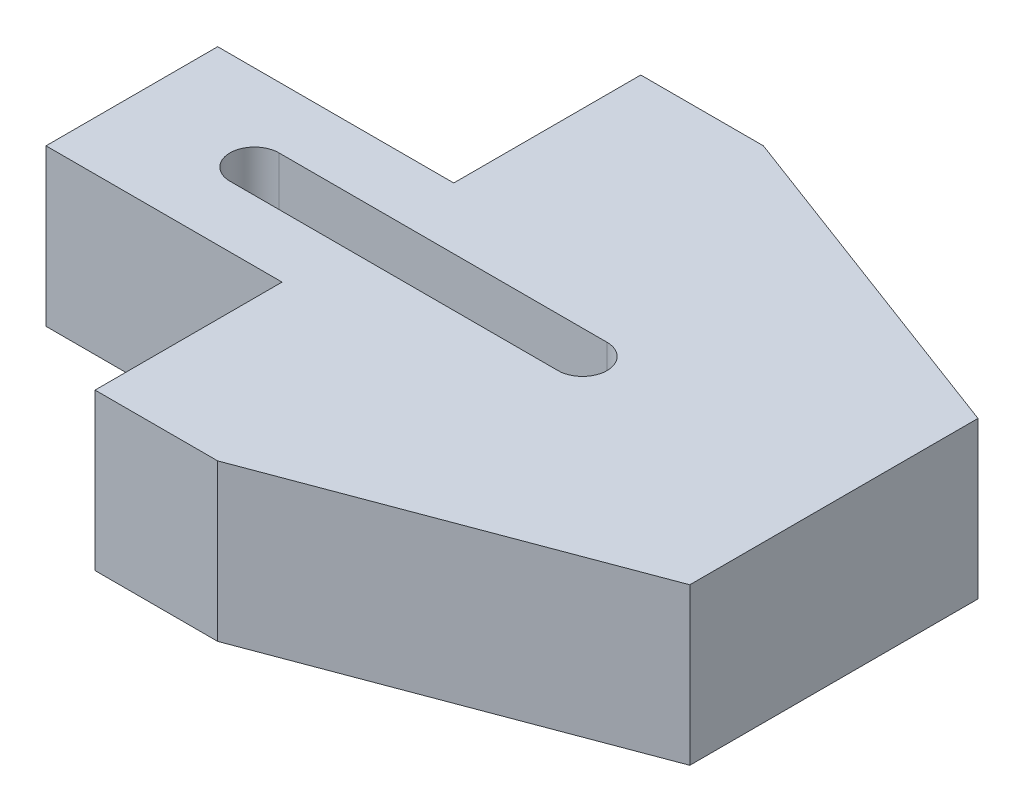
SolidWorks part; units mm, degrees
ref_plane "Front Plane" through (0, 0, 0) normal (0, 0, 1) x (1, 0, 0)
ref_plane "Top Plane" through (0, 0, 0) normal (0, 1, 0) x (1, 0, 0)
ref_plane "Right Plane" through (0, 0, 0) normal (1, 0, 0) x (0, 0, -1)
sketch "Sketch1" plane through (0, 0, 0) normal (0, 1, 0) x (1, 0, 0)
  line L0 (-22.9, 0) -> (-22.9, 2.8)
  line L1 (-22.9, 2.8) -> (-15.2, 2.8)
  line L2 (-15.2, 2.8) -> (-15.2, 8.9)
  line L3 (-15.2, 8.9) -> (-11.2, 8.9)
  line L4 (-11.2, 8.9) -> (0, 4.7)
  line L5 (0, 4.7) -> (0, 0)
  line L6 (0, 0) -> (-22.9, 0)
  point P11 (-22.9, 1.4)
  dimension "D1" = 22.9
  dimension "D2" = 15.2
  dimension "D3" = 2.8
  dimension "D4" = 8.9
  dimension "D5" = 4.7
  dimension "D6" = 4
extrude "Boss-Extrude1" add sketch "Sketch1" along normal mid plane 5.1
mirror "Mirror1" about plane through (0, 0, 0) normal (0, 0, 1) of "Boss-Extrude1"
sketch "Sketch2" plane through (0, 2.55, 0) normal (0, 1, 0) x (1, 0, 0)
  line L0 (-18.9, 0) -> (-8.2, 0) construction
  line L1 (-18.9, 0.8) -> (-8.2, 0.8)
  line L2 (-18.9, -0.8) -> (-8.2, -0.8)
  line L3 (-15.2, 8.9) -> (-15.2, 2.8) construction
  arc A0 (-18.9, 0.8) -> (-18.9, -0.8) centre (-18.9, 0) ccw
  arc A1 (-8.2, -0.8) -> (-8.2, 0.8) centre (-8.2, 0) ccw
  point P2 (-13.55, 0)
  dimension "D1" = 10.7
  dimension "D2" = 1.6
  dimension "D3" = 7
extrude "Cut-Extrude1" cut sketch "Sketch2" against normal through all
